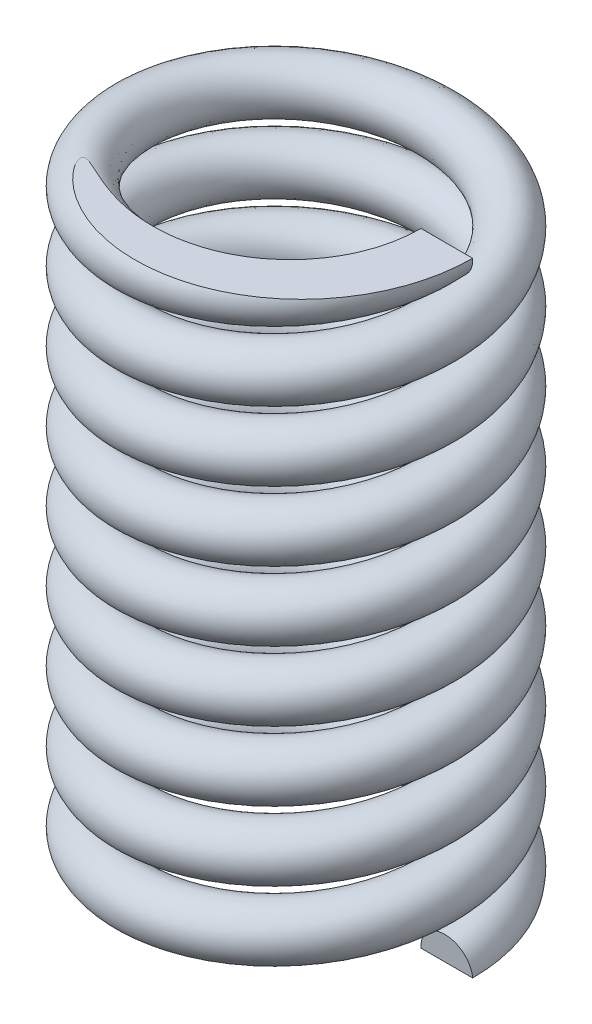
SolidWorks part; units mm, degrees
material "Ductile Iron (SN)"
ref_plane "Front Plane" through (0, 0, 0) normal (0, 0, 1) x (1, 0, 0)
ref_plane "Top Plane" through (0, 0, 0) normal (0, 1, 0) x (1, 0, 0)
ref_plane "Right Plane" through (0, 0, 0) normal (1, 0, 0) x (0, 0, -1)
sketch "Sketch1"
  dimension "D1" = 78.5121
ref_plane "Plane1" through (0, 59.1163, 0) normal (0, -1, 0) x (-1, 0, 0)
sketch "Sketch2" plane through (0, 59.1163, 0) normal (0, -1, 0) x (-1, 0, 0)
  circle A0 centre (0, 0) radius 19
  dimension "D1" = 38
curve "Helix/Spiral1" pitch 8.7236 height 78.5121 turns 9
ref_plane "Plane2" through (19, 59.1163, 0) normal (0, 0.0729, -0.9973) x (-1, 0, 0)
sketch "Sketch3" plane through (19, 59.1163, 0) normal (0, 0.0729, -0.9973) x (-1, 0, 0)
  circle A0 centre (0, 0) radius 3.25
  dimension "D1" = 6.5
sweep "Sweep1" add profiles "Sketch3" path "Helix/Spiral1"
sketch "Sketch4" plane through (0, 0, 0) normal (0, 0, 1) x (1, 0, 0)
  line L1 (-27.5, 152.6284) -> (27.5, 152.6284)
  line L2 (-27.5, 152.6284) -> (-27.5, 137.6284)
  line L3 (-27.5, 137.6284) -> (27.5, 137.6284)
  line L4 (27.5, 152.6284) -> (27.5, 137.6284)
  line L5 (-27.5, 152.6284) -> (27.5, 137.6284) construction
  line L6 (-27.5, 137.6284) -> (27.5, 152.6284) construction
  line L7 (27.5, 44.1163) -> (-27.5, 44.1163)
  line L8 (27.5, 44.1163) -> (27.5, 59.1163)
  line L9 (27.5, 59.1163) -> (-27.5, 59.1163)
  line L10 (-27.5, 44.1163) -> (-27.5, 59.1163)
  line L11 (27.5, 44.1163) -> (-27.5, 59.1163) construction
  line L12 (27.5, 59.1163) -> (-27.5, 44.1163) construction
  ellipse E0 centre (19, 137.6284) end of major axis (15.75, 137.6284) minor radius 3.2414 construction
  point P0 (0, 145.1284)
  point P5 (19, 137.6284)
  point P13 (0, 51.6163)
  dimension "D1" = 55
  dimension "D2" = 15
  dimension "D3" = 15
extrude "Cut-Extrude1" cut sketch "Sketch4" against normal through all both and the other way through all
equation "\"D3@Helix/Spiral1\"=\"D1@Sketch1\""
